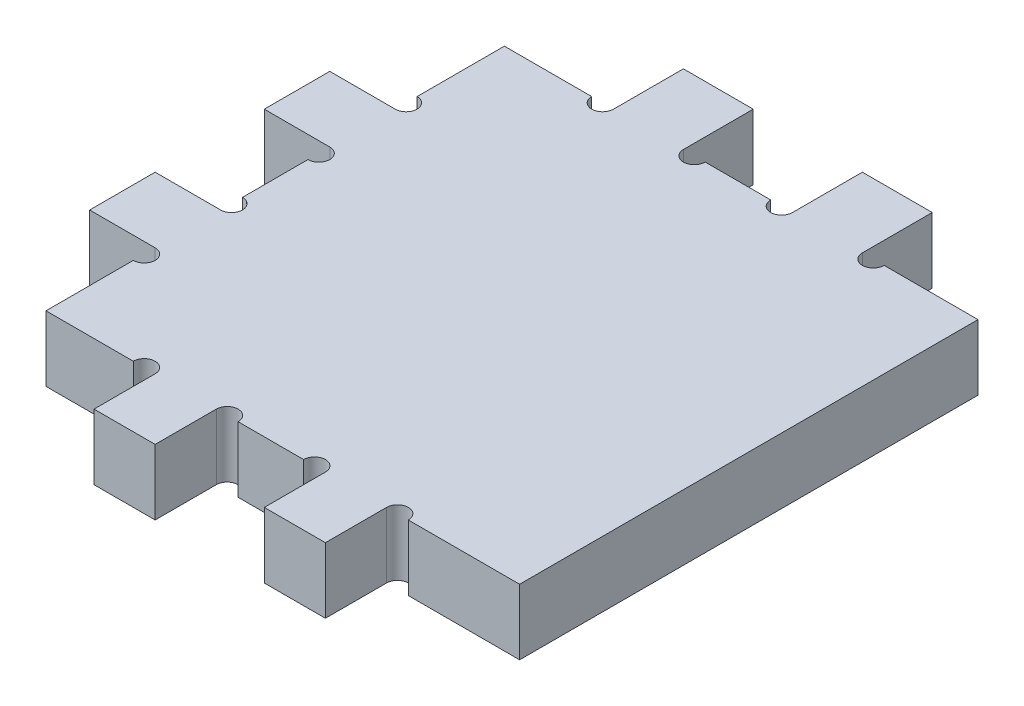
SolidWorks part; units mm, degrees
ref_plane "Front Plane" through (0, 0, 0) normal (0, 0, 1) x (1, 0, 0)
ref_plane "Top Plane" through (0, 0, 0) normal (0, 1, 0) x (1, 0, 0)
ref_plane "Right Plane" through (0, 0, 0) normal (1, 0, 0) x (0, 0, -1)
sketch "Sketch1" plane through (0, 0, 0) normal (0, 1, 0) x (1, 0, 0)
  line L0 (-31.75, 39.5584) -> (-50.8, 39.5584)
  line L1 (-50.8, 39.5584) -> (-50.8, 20.5084)
  line L2 (-50.8, 20.5084) -> (-31.75, 20.5084)
  line L3 (-31.75, 14.1584) -> (-31.75, -4.8916)
  line L4 (-31.75, -11.2416) -> (-50.8, -11.2416)
  line L5 (-50.8, -11.2416) -> (-50.8, -30.2916)
  line L6 (-50.8, -30.2916) -> (-31.75, -30.2916)
  line L7 (-31.75, -36.6416) -> (-31.75, -62.0416)
  line L8 (-31.75, -62.0416) -> (-6.35, -62.0416)
  line L9 (-31.75, 45.9084) -> (-31.75, 71.3084)
  line L10 (-31.75, 71.3084) -> (-6.35, 71.3084)
  line L11 (0, 71.3084) -> (0, 91.6284)
  line L12 (0, 91.6284) -> (20.32, 91.6284)
  line L13 (20.32, 91.6284) -> (20.32, 71.3084)
  line L14 (52.07, 71.3084) -> (52.07, 91.6284)
  line L15 (52.07, 91.6284) -> (72.39, 91.6284)
  line L16 (72.39, 91.6284) -> (72.39, 71.3084)
  line L17 (26.67, 71.3084) -> (45.72, 71.3084)
  line L18 (78.74, 71.3084) -> (106.0271, 71.3084)
  line L19 (106.0271, 71.3084) -> (106.0271, -62.0416)
  line L20 (106.0271, 4.6334) -> (87.0994, 4.6334) construction
  line L21 (0, -62.0416) -> (0, -79.8216)
  line L22 (0, -79.8216) -> (17.78, -79.8216)
  line L23 (17.78, -79.8216) -> (17.78, -62.0416)
  line L24 (49.53, -62.0416) -> (49.53, -79.8216)
  line L25 (49.53, -79.8216) -> (67.31, -79.8216)
  line L26 (67.31, -79.8216) -> (67.31, -62.0416)
  line L28 (24.13, -62.0416) -> (43.18, -62.0416)
  line L29 (73.66, -62.0416) -> (106.0271, -62.0416)
  arc A0 (-31.75, 39.5584) -> (-31.75, 45.9084) centre (-31.75, 42.7334) ccw
  arc A1 (-31.75, 14.1584) -> (-31.75, 20.5084) centre (-31.75, 17.3334) ccw
  arc A2 (-31.75, -11.2416) -> (-31.75, -4.8916) centre (-31.75, -8.0666) ccw
  arc A3 (-31.75, -36.6416) -> (-31.75, -30.2916) centre (-31.75, -33.4666) ccw
  arc A4 (-6.35, 71.3084) -> (0, 71.3084) centre (-3.175, 71.3084) ccw
  arc A5 (20.32, 71.3084) -> (26.67, 71.3084) centre (23.495, 71.3084) ccw
  arc A6 (45.72, 71.3084) -> (52.07, 71.3084) centre (48.895, 71.3084) ccw
  arc A7 (72.39, 71.3084) -> (78.74, 71.3084) centre (75.565, 71.3084) ccw
  arc A11 (-6.35, -62.0416) -> (0, -62.0416) centre (-3.175, -62.0416) cw
  arc A12 (17.78, -62.0416) -> (24.13, -62.0416) centre (20.955, -62.0416) cw
  arc A13 (43.18, -62.0416) -> (49.53, -62.0416) centre (46.355, -62.0416) cw
  arc A14 (67.31, -62.0416) -> (73.66, -62.0416) centre (70.485, -62.0416) cw
  point P55 (0, 0)
  point P56 (0, 0)
  point P57 (0, 0)
  point P58 (43.18, -17.0719)
  point P59 (0, 0)
  point P60 (0, 0)
  point P61 (0, 0)
  point P62 (0, 0)
  point P63 (0, 0)
  dimension "D3" = 3.175
  dimension "D1" = 19.05
  dimension "D2" = 19.05
  dimension "D4" = 6.35
  dimension "D5" = 50.8
  dimension "D6" = 6.35
  dimension "D7" = 25.4
  dimension "D8" = 20.32
  dimension "D10" = 19.05
  dimension "D12" = 6.35
  dimension "D13" = 17.78
  dimension "D14" = 25.4
  dimension "D15" = 6.35
  dimension "D16" = 19.05
  dimension "D9" = 2
extrude "Boss-Extrude1" add sketch "Sketch1" along normal blind 19.05
